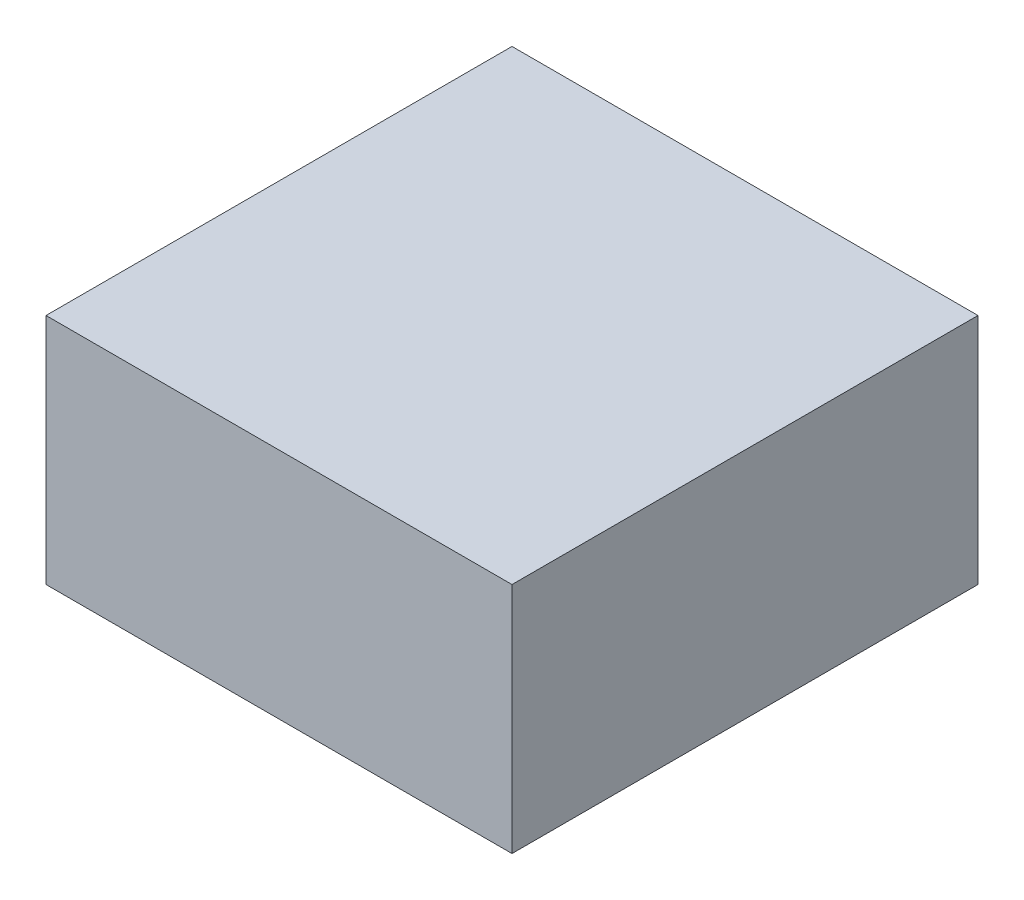
SolidWorks part; units mm, degrees
ref_plane "Front Plane" through (0, 0, 0) normal (0, 0, 1) x (1, 0, 0)
ref_plane "Top Plane" through (0, 0, 0) normal (0, 1, 0) x (1, 0, 0)
ref_plane "Right Plane" through (0, 0, 0) normal (1, 0, 0) x (0, 0, -1)
sketch "Sketch1" plane through (0, 0, 0) normal (0, 1, 0) x (1, 0, 0)
  line L1 (-1500, -1500) -> (1500, -1500)
  line L2 (-1500, -1500) -> (-1500, 1500)
  line L3 (-1500, 1500) -> (1500, 1500)
  line L4 (1500, -1500) -> (1500, 1500)
  line L5 (0, 1500) -> (0, -1500) construction
  line L6 (-1500, 0) -> (1500, 0) construction
  point P0 (0, 0)
  dimension "D1" = 3000
extrude "Boss-Extrude2" add sketch "Sketch1" along normal mid plane 1500
